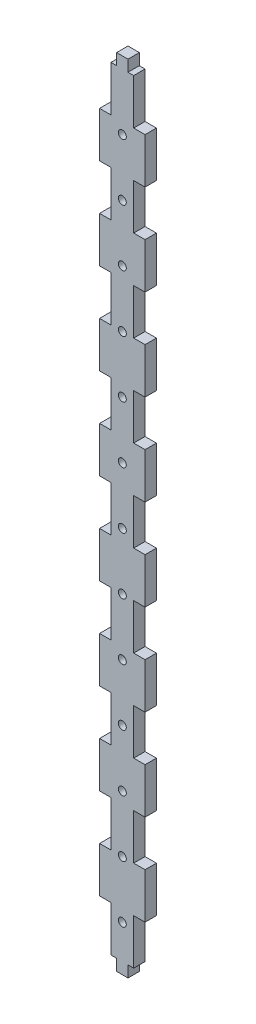
SolidWorks part; units mm, degrees
ref_plane "Front Plane" through (0, 0, 0) normal (0, 0, 1) x (1, 0, 0)
ref_plane "Top Plane" through (0, 0, 0) normal (0, 1, 0) x (1, 0, 0)
ref_plane "Right Plane" through (0, 0, 0) normal (1, 0, 0) x (0, 0, -1)
sketch "Model" plane through (0, 0, 0) normal (0, 0, 1) x (1, 0, 0)
  line L0 (8.2247, 172.5) -> (8.2247, 167.5)
  line L1 (13.2247, 172.5) -> (8.2247, 172.5)
  line L2 (13.2247, 167.5) -> (13.2247, 172.5)
  line L3 (15.7247, 167.5) -> (13.2247, 167.5)
  line L4 (15.7247, 147.5) -> (15.7247, 167.5)
  line L5 (20.7247, 147.5) -> (15.7247, 147.5)
  line L6 (20.7247, 127.5) -> (20.7247, 147.5)
  line L7 (15.7247, 127.5) -> (20.7247, 127.5)
  line L8 (15.7247, 107.5) -> (15.7247, 127.5)
  line L9 (20.7247, 107.5) -> (15.7247, 107.5)
  line L10 (20.7247, 87.5) -> (20.7247, 107.5)
  line L11 (15.7247, 87.5) -> (20.7247, 87.5)
  line L12 (15.7247, 67.5) -> (15.7247, 87.5)
  line L13 (20.7247, 67.5) -> (15.7247, 67.5)
  line L14 (20.7247, 47.5) -> (20.7247, 67.5)
  line L15 (15.7247, 47.5) -> (20.7247, 47.5)
  line L16 (15.7247, 27.5) -> (15.7247, 47.5)
  line L17 (20.7247, 27.5) -> (15.7247, 27.5)
  line L18 (20.7247, 7.5) -> (20.7247, 27.5)
  line L19 (15.7247, 7.5) -> (20.7247, 7.5)
  line L20 (15.7247, -12.5) -> (15.7247, 7.5)
  line L21 (20.7247, -12.5) -> (15.7247, -12.5)
  line L22 (20.7247, -32.5) -> (20.7247, -12.5)
  line L23 (15.7247, -32.5) -> (20.7247, -32.5)
  line L24 (15.7247, -52.5) -> (15.7247, -32.5)
  line L25 (20.7247, -52.5) -> (15.7247, -52.5)
  line L26 (20.7247, -72.5) -> (20.7247, -52.5)
  line L27 (15.7247, -72.5) -> (20.7247, -72.5)
  line L28 (15.7247, -92.5) -> (15.7247, -72.5)
  line L29 (20.7247, -92.5) -> (15.7247, -92.5)
  line L30 (20.7247, -112.5) -> (20.7247, -92.5)
  line L31 (15.7247, -112.5) -> (20.7247, -112.5)
  line L32 (15.7247, -132.5) -> (15.7247, -112.5)
  line L33 (20.7247, -132.5) -> (15.7247, -132.5)
  line L34 (20.7247, -152.5) -> (20.7247, -132.5)
  line L35 (15.7247, -152.5) -> (20.7247, -152.5)
  line L36 (15.7247, -172.5) -> (15.7247, -152.5)
  line L37 (13.2247, -172.5) -> (15.7247, -172.5)
  line L38 (13.2247, -177.5) -> (13.2247, -172.5)
  line L39 (8.2247, -177.5) -> (13.2247, -177.5)
  line L40 (8.2247, -172.5) -> (8.2247, -177.5)
  line L41 (5.7247, -172.5) -> (8.2247, -172.5)
  line L42 (5.7247, -152.5) -> (5.7247, -172.5)
  line L43 (0.7247, -152.5) -> (5.7247, -152.5)
  line L44 (0.7247, -132.5) -> (0.7247, -152.5)
  line L45 (5.7247, -132.5) -> (0.7247, -132.5)
  line L46 (5.7247, -112.5) -> (5.7247, -132.5)
  line L47 (0.7247, -112.5) -> (5.7247, -112.5)
  line L48 (0.7247, -92.5) -> (0.7247, -112.5)
  line L49 (5.7247, -92.5) -> (0.7247, -92.5)
  line L50 (5.7247, -72.5) -> (5.7247, -92.5)
  line L51 (0.7247, -72.5) -> (5.7247, -72.5)
  line L52 (0.7247, -52.5) -> (0.7247, -72.5)
  line L53 (5.7247, -52.5) -> (0.7247, -52.5)
  line L54 (5.7247, -32.5) -> (5.7247, -52.5)
  line L55 (0.7247, -32.5) -> (5.7247, -32.5)
  line L56 (0.7247, -12.5) -> (0.7247, -32.5)
  line L57 (5.7247, -12.5) -> (0.7247, -12.5)
  line L58 (5.7247, 7.5) -> (5.7247, -12.5)
  line L59 (0.7247, 7.5) -> (5.7247, 7.5)
  line L60 (0.7247, 27.5) -> (0.7247, 7.5)
  line L61 (5.7247, 27.5) -> (0.7247, 27.5)
  line L62 (5.7247, 47.5) -> (5.7247, 27.5)
  line L63 (0.7247, 47.5) -> (5.7247, 47.5)
  line L64 (0.7247, 67.5) -> (0.7247, 47.5)
  line L65 (5.7247, 67.5) -> (0.7247, 67.5)
  line L66 (5.7247, 87.5) -> (5.7247, 67.5)
  line L67 (0.7247, 87.5) -> (5.7247, 87.5)
  line L68 (0.7247, 107.5) -> (0.7247, 87.5)
  line L69 (5.7247, 107.5) -> (0.7247, 107.5)
  line L70 (5.7247, 127.5) -> (5.7247, 107.5)
  line L71 (0.7247, 127.5) -> (5.7247, 127.5)
  line L72 (0.7247, 147.5) -> (0.7247, 127.5)
  line L73 (5.7247, 147.5) -> (0.7247, 147.5)
  line L74 (5.7247, 167.5) -> (5.7247, 147.5)
  line L75 (8.2247, 167.5) -> (5.7247, 167.5)
  circle A0 centre (10.7247, 142.5) radius 1.75
  circle A1 centre (10.7247, 92.5) radius 1.75
  circle A2 centre (10.7247, 42.5) radius 1.75
  circle A3 centre (10.7247, -7.5) radius 1.75
  circle A4 centre (10.7247, -57.5) radius 1.75
  circle A5 centre (10.7247, -107.5) radius 1.75
  circle A6 centre (10.7247, -157.5) radius 1.75
  circle A7 centre (10.7247, -132.5) radius 1.75
  circle A8 centre (10.7247, -82.5) radius 1.75
  circle A9 centre (10.7247, -32.5) radius 1.75
  circle A10 centre (10.7247, 17.5) radius 1.75
  circle A11 centre (10.7247, 67.5) radius 1.75
  circle A12 centre (10.7247, 117.5) radius 1.75
extrude "Boss-Extrude1" add sketch "Model" along normal blind 5
